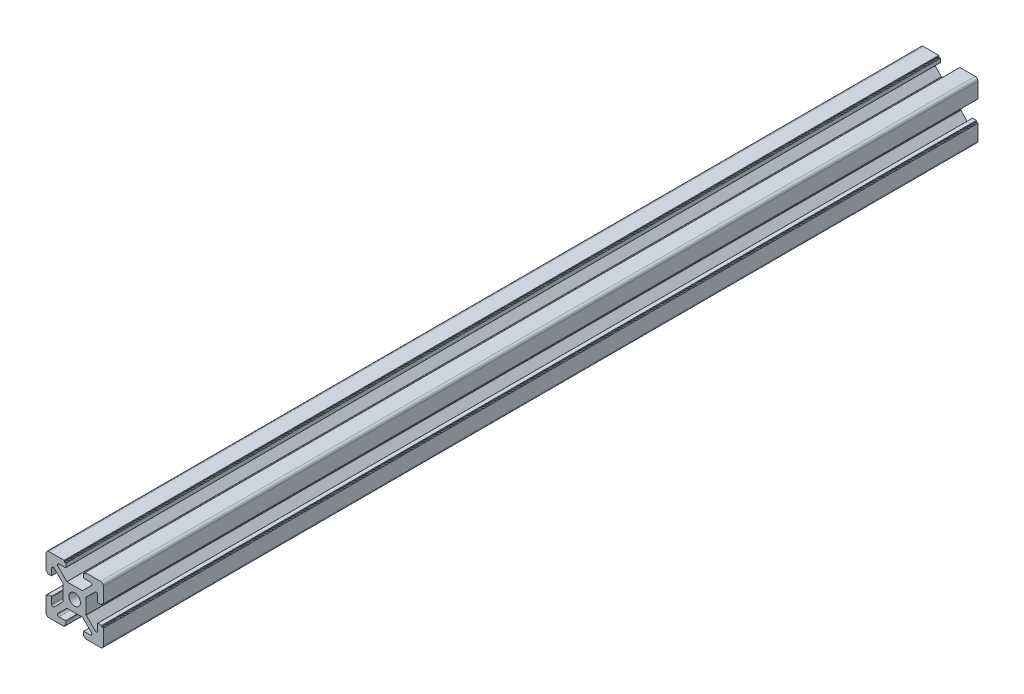
SolidWorks part; units mm, degrees
ref_plane "Plane1" through (0, 0, 0) normal (0, 0, 1) x (1, 0, 0)
ref_plane "Plane2" through (0, 0, 0) normal (0, 1, 0) x (1, 0, 0)
ref_plane "Plane3" through (0, 0, 0) normal (1, 0, 0) x (0, 0, -1)
sketch "Sketch1" plane through (0, 0, 0) normal (0, 0, 1) x (1, 0, 0)
  line L0 (-26.4662, 0) -> (25.1675, 0) construction
  line L1 (0, 16.7588) -> (0, -17.8201) construction
  line L2 (-10, 9) -> (-10, 3.7)
  line L3 (8, -5.5201) -> (8, -3.2)
  line L4 (-4, 0) -> (-4, 2.6858)
  line L5 (-2.6858, 4) -> (2.6858, 4)
  line L6 (4, 0) -> (4, 2.6858)
  line L7 (-4, -4) -> (4, 4) construction
  line L8 (-4, 4) -> (4, -4) construction
  line L9 (-9, 10) -> (-3.7, 10)
  line L10 (-8, 5.5201) -> (-8, 3.2)
  line L11 (10, -9) -> (10, -3.7)
  line L12 (9.6, -3.6) -> (9.9, -3.6)
  line L13 (-10, 10) -> (10, -10) construction
  line L14 (-10, -10) -> (10, 10) construction
  line L15 (9.5, -3.2) -> (9.5, -3.5)
  line L16 (8.1, -3.1) -> (9.4, -3.1)
  line L17 (-5.5201, 8) -> (-3.2, 8)
  line L18 (-7.1464, 5.8737) -> (-4.0293, 2.7565)
  line L19 (-5.8737, 7.1464) -> (-2.7565, 4.0293)
  line L20 (-3.1, 8.1) -> (-3.1, 9.4)
  line L21 (-3.2, 9.5) -> (-3.5, 9.5)
  line L22 (-3.6, 9.6) -> (-3.6, 9.9)
  line L23 (3.1, 8.1) -> (3.1, 9.4)
  line L24 (3.2, 9.5) -> (3.5, 9.5)
  line L25 (3.6, 9.6) -> (3.6, 9.9)
  line L26 (2.7565, 4.0293) -> (5.8737, 7.1464)
  line L27 (4.0293, 2.7565) -> (7.1464, 5.8737)
  line L28 (-8, 8) -> (8, 8) construction
  line L29 (-8, 8) -> (-8, -8) construction
  line L30 (8, 8) -> (8, -8) construction
  line L31 (3.7, 10) -> (9, 10)
  line L32 (-9, 10) -> (9, 10) construction
  line L33 (3.2, 8) -> (5.5201, 8)
  line L34 (-9.5, 3.2) -> (-9.5, 3.5)
  line L35 (-9.6, 3.6) -> (-9.9, 3.6)
  line L36 (-8.1, 3.1) -> (-9.4, 3.1)
  line L37 (-9, -10) -> (9, -10) construction
  line L38 (-10, 9) -> (-10, -9) construction
  line L39 (-8, -8) -> (8, -8) construction
  line L40 (10, 9) -> (10, -9) construction
  line L41 (8.1, 3.1) -> (9.4, 3.1)
  line L42 (9.5, 3.2) -> (9.5, 3.5)
  line L43 (9.6, 3.6) -> (9.9, 3.6)
  line L44 (10, 9) -> (10, 3.7)
  line L45 (8, 5.5201) -> (8, 3.2)
  line L46 (-8.1, -3.1) -> (-9.4, -3.1)
  line L47 (-9.6, -3.6) -> (-9.9, -3.6)
  line L48 (-9.5, -3.2) -> (-9.5, -3.5)
  line L49 (3.2, -8) -> (5.5201, -8)
  line L50 (3.7, -10) -> (9, -10)
  line L51 (4.0293, -2.7565) -> (7.1464, -5.8737)
  line L52 (2.7565, -4.0293) -> (5.8737, -7.1464)
  line L53 (3.6, -9.6) -> (3.6, -9.9)
  line L54 (3.2, -9.5) -> (3.5, -9.5)
  line L55 (3.1, -8.1) -> (3.1, -9.4)
  line L56 (-3.6, -9.6) -> (-3.6, -9.9)
  line L57 (-3.2, -9.5) -> (-3.5, -9.5)
  line L58 (-3.1, -8.1) -> (-3.1, -9.4)
  line L59 (-5.8737, -7.1464) -> (-2.7565, -4.0293)
  line L60 (-7.1464, -5.8737) -> (-4.0293, -2.7565)
  line L61 (-5.5201, -8) -> (-3.2, -8)
  line L62 (-8, -5.5201) -> (-8, -3.2)
  line L63 (-9, -10) -> (-3.7, -10)
  line L64 (-2.6858, -4) -> (2.6858, -4)
  line L65 (-10, -9) -> (-10, -3.7)
  line L66 (-4, 0) -> (-4, -2.6858)
  line L68 (4, 0) -> (4, -2.6858)
  circle A0 centre (0, 0) radius 2
  arc A1 (-10, 9) -> (-9, 10) centre (-9, 9) cw
  arc A2 (10, -3.7) -> (9.9, -3.6) centre (9.9, -3.7) ccw
  arc A3 (-10, -9) -> (-9, -10) centre (-9, -9) ccw construction
  arc A4 (10, 9) -> (9, 10) centre (9, 9) ccw
  arc A5 (-8, -8) -> (-8, -8) centre (-8, -8) ccw
  arc A6 (8, -8) -> (8, -8) centre (8, -8) cw
  arc A7 (8, 8) -> (8, 8) centre (8, 8) ccw
  arc A8 (-8, 8) -> (-8, 8) centre (-8, 8) cw
  arc A9 (-5.5201, 8) -> (-5.8737, 7.1464) centre (-5.5201, 7.5) ccw
  arc A10 (5.5201, 8) -> (5.8737, 7.1464) centre (5.5201, 7.5) cw
  arc A11 (-8, 5.5201) -> (-7.1464, 5.8737) centre (-7.5, 5.5201) cw
  arc A12 (8, 5.5201) -> (7.1464, 5.8737) centre (7.5, 5.5201) ccw
  arc A13 (-3.6, 9.9) -> (-3.7, 10) centre (-3.7, 9.9) ccw
  arc A14 (-3.5, 9.5) -> (-3.6, 9.6) centre (-3.5, 9.6) cw
  arc A15 (-3.2, 9.5) -> (-3.1, 9.4) centre (-3.2, 9.4) cw
  arc A16 (-3.1, 8.1) -> (-3.2, 8) centre (-3.2, 8.1) cw
  arc A17 (3.2, 8) -> (3.1, 8.1) centre (3.2, 8.1) cw
  arc A18 (3.2, 9.5) -> (3.1, 9.4) centre (3.2, 9.4) ccw
  arc A19 (3.5, 9.5) -> (3.6, 9.6) centre (3.5, 9.6) ccw
  arc A20 (3.7, 10) -> (3.6, 9.9) centre (3.7, 9.9) ccw
  arc A21 (-2.6858, 4) -> (-2.7565, 4.0293) centre (-2.6858, 4.1) cw
  arc A22 (-4, 2.6858) -> (-4.0293, 2.7565) centre (-4.1, 2.6858) ccw
  arc A23 (2.6858, 4) -> (2.7565, 4.0293) centre (2.6858, 4.1) ccw
  arc A24 (4.0293, 2.7565) -> (4, 2.6858) centre (4.1, 2.6858) ccw
  arc A25 (-9.5, 3.2) -> (-9.4, 3.1) centre (-9.4, 3.2) ccw
  arc A26 (-9.5, 3.5) -> (-9.6, 3.6) centre (-9.6, 3.5) ccw
  arc A27 (-9.9, 3.6) -> (-10, 3.7) centre (-9.9, 3.7) cw
  arc A28 (-8.1, 3.1) -> (-8, 3.2) centre (-8.1, 3.2) ccw
  arc A29 (8, 3.2) -> (8.1, 3.1) centre (8.1, 3.2) ccw
  arc A30 (9.5, 3.2) -> (9.4, 3.1) centre (9.4, 3.2) cw
  arc A31 (9.5, 3.5) -> (9.6, 3.6) centre (9.6, 3.5) cw
  arc A32 (10, 3.7) -> (9.9, 3.6) centre (9.9, 3.7) cw
  arc A33 (10, -9) -> (9, -10) centre (9, -9) cw construction
  arc A34 (9.5, -3.5) -> (9.6, -3.6) centre (9.6, -3.5) ccw
  arc A35 (9.5, -3.2) -> (9.4, -3.1) centre (9.4, -3.2) ccw
  arc A36 (8, -3.2) -> (8.1, -3.1) centre (8.1, -3.2) cw
  arc A37 (-8.1, -3.1) -> (-8, -3.2) centre (-8.1, -3.2) cw
  arc A38 (-9.9, -3.6) -> (-10, -3.7) centre (-9.9, -3.7) ccw
  arc A39 (-9.5, -3.5) -> (-9.6, -3.6) centre (-9.6, -3.5) cw
  arc A40 (-9.5, -3.2) -> (-9.4, -3.1) centre (-9.4, -3.2) cw
  arc A41 (4.0293, -2.7565) -> (4, -2.6858) centre (4.1, -2.6858) cw
  arc A42 (2.6858, -4) -> (2.7565, -4.0293) centre (2.6858, -4.1) cw
  arc A43 (-4, -2.6858) -> (-4.0293, -2.7565) centre (-4.1, -2.6858) cw
  arc A44 (-2.6858, -4) -> (-2.7565, -4.0293) centre (-2.6858, -4.1) ccw
  arc A45 (3.7, -10) -> (3.6, -9.9) centre (3.7, -9.9) cw
  arc A46 (3.5, -9.5) -> (3.6, -9.6) centre (3.5, -9.6) cw
  arc A47 (3.2, -9.5) -> (3.1, -9.4) centre (3.2, -9.4) cw
  arc A48 (3.2, -8) -> (3.1, -8.1) centre (3.2, -8.1) ccw
  arc A49 (-3.1, -8.1) -> (-3.2, -8) centre (-3.2, -8.1) ccw
  arc A50 (-3.2, -9.5) -> (-3.1, -9.4) centre (-3.2, -9.4) ccw
  arc A51 (-3.5, -9.5) -> (-3.6, -9.6) centre (-3.5, -9.6) ccw
  arc A52 (-3.6, -9.9) -> (-3.7, -10) centre (-3.7, -9.9) cw
  arc A53 (8, -5.5201) -> (7.1464, -5.8737) centre (7.5, -5.5201) cw
  arc A54 (-8, -5.5201) -> (-7.1464, -5.8737) centre (-7.5, -5.5201) ccw
  arc A55 (5.5201, -8) -> (5.8737, -7.1464) centre (5.5201, -7.5) ccw
  arc A56 (-5.5201, -8) -> (-5.8737, -7.1464) centre (-5.5201, -7.5) cw
  arc A57 (10, -9) -> (9, -10) centre (9, -9) cw
  arc A58 (-10, -9) -> (-9, -10) centre (-9, -9) ccw
  point P0 (0, 0)
  point P70 (3.1, 8.75)
  point P72 (-3.6, 10)
  point P75 (-3.6, 9.5)
  point P82 (3.1, 8)
  point P87 (3.6, 9.5)
  point P90 (3.6, 10)
  point P198 (3.6, -10)
  point P199 (3.6, -9.5)
  point P200 (3.1, -8)
  point P201 (-3.6, -9.5)
  point P202 (-3.6, -10)
extrude "Boss-Extrude1" add sketch "Sketch1" along normal blind 305 contours L65 A58 L63 A52 L56 A51 L57 A50 L58 A49 L61 A56 L59 A44 L64 A42 L52 A55 L49 A48 L55 A47 L54 A46 L53 A45 L50 A57 L11 A2 L12 A34 L15 A35 L16 A36 L3 A53 L51 A41 L68 L6 A24 L27 A12 L45 A29 L41 A30 L42 A31
